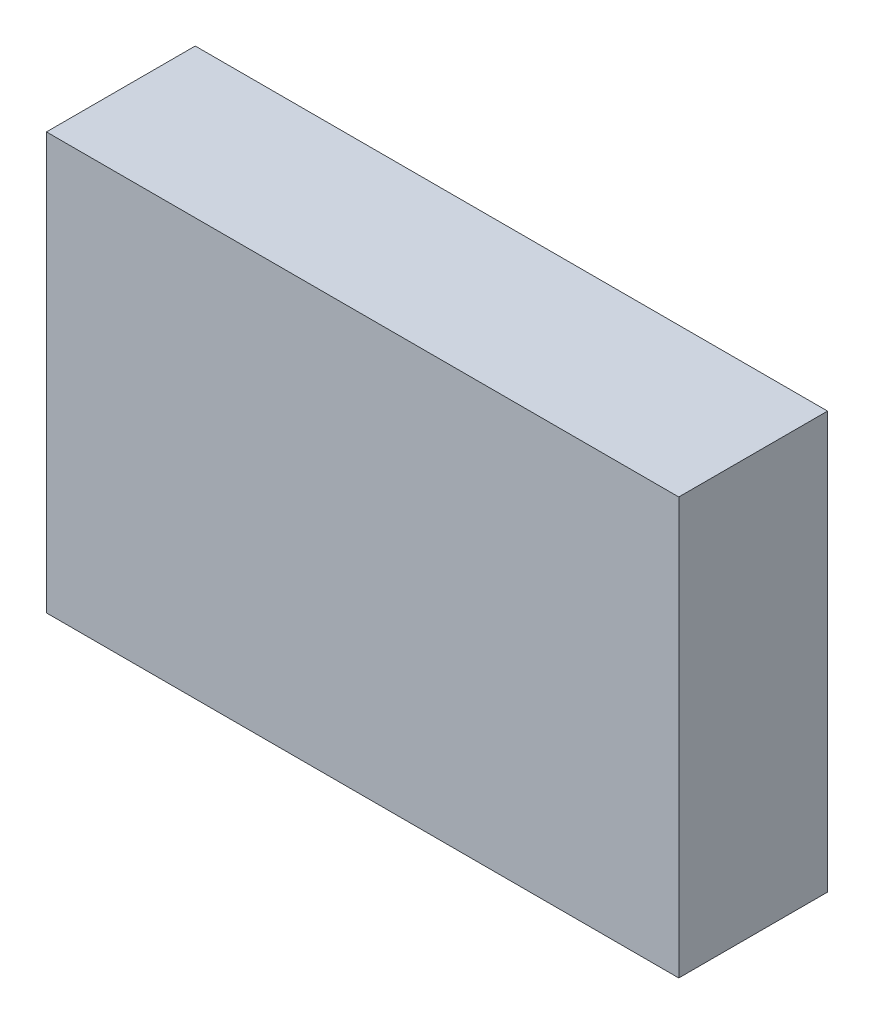
SolidWorks part; units mm, degrees
ref_plane "Front Plane" through (0, 0, 0) normal (0, 0, 1) x (1, 0, 0)
ref_plane "Top Plane" through (0, 0, 0) normal (0, 1, 0) x (1, 0, 0)
ref_plane "Right Plane" through (0, 0, 0) normal (1, 0, 0) x (0, 0, -1)
sketch "Sketch1" plane through (0, 0, 0) normal (0, 0, 1) x (1, 0, 0)
  line L1 (0, 0) -> (85, 0)
  line L2 (0, 0) -> (0, -56)
  line L3 (0, -56) -> (85, -56)
  line L4 (85, 0) -> (85, -56)
extrude "Boss-Extrude1" add sketch "Sketch1" along normal blind 20
